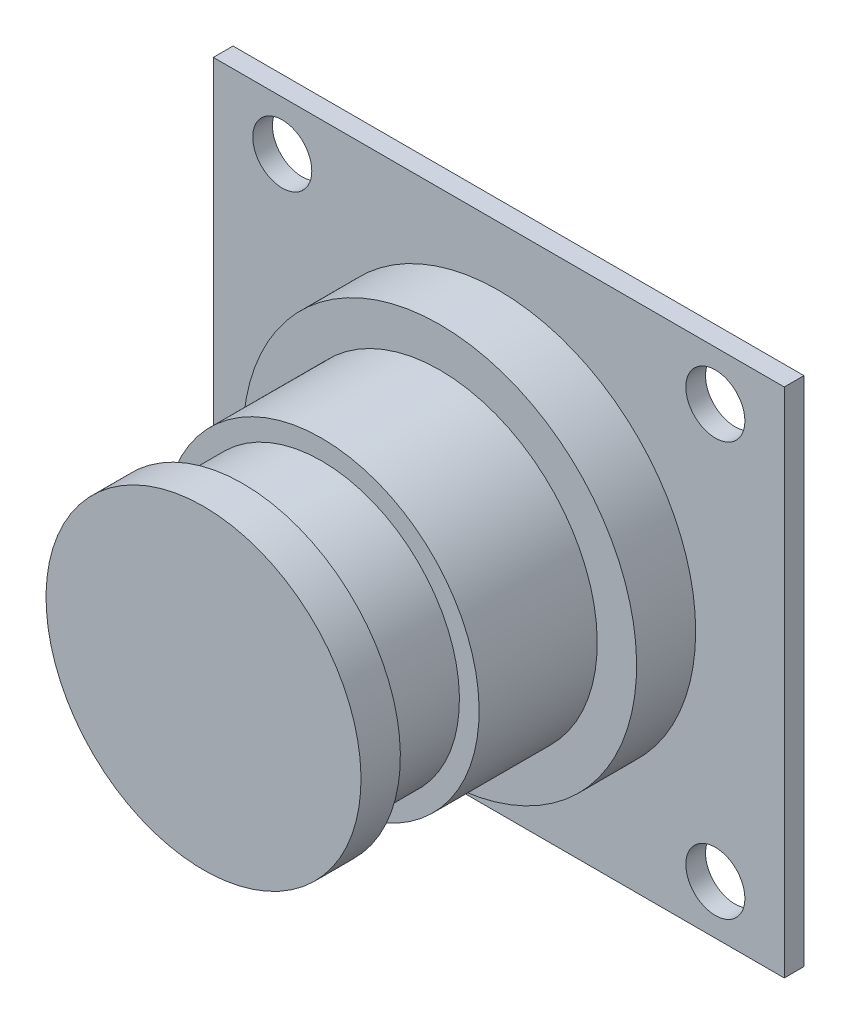
SolidWorks part; units mm, degrees
material "自定义塑料"
ref_plane "前视基准面" through (0, 0, 0) normal (0, 0, 1) x (1, 0, 0)
ref_plane "上视基准面" through (0, 0, 0) normal (0, 1, 0) x (1, 0, 0)
ref_plane "右视基准面" through (0, 0, 0) normal (1, 0, 0) x (0, 0, -1)
other "Configuration Table"
sketch "草图1" plane through (0, 0, 0) normal (0, 0, 1) x (1, 0, 0)
  line L0 (-19.7925, 0) -> (25.058, 0) construction
  line L1 (-14.5, 13) -> (14.5, 13)
  line L2 (-14.5, 13) -> (-14.5, -13)
  line L3 (-14.5, -13) -> (14.5, -13)
  line L4 (14.5, 13) -> (14.5, -13)
  line L5 (-11, 10.5) -> (11, 10.5) construction
  line L6 (-11, 10.5) -> (-11, -10.5) construction
  line L7 (-11, -10.5) -> (11, -10.5) construction
  line L8 (11, 10.5) -> (11, -10.5) construction
  line L9 (0, 23.3134) -> (0, -16.2925) construction
  circle A0 centre (-11, 10.5) radius 1.5
  circle A1 centre (11, 10.5) radius 1.5
  circle A2 centre (11, -10.5) radius 1.5
  circle A3 centre (-11, -10.5) radius 1.5
  dimension "D1" = 3
  dimension "D2" = 26
  dimension "D3" = 29
  dimension "D4" = 21
  dimension "D5" = 22
extrude "凸台-拉伸1" add sketch "草图1" along normal blind 1
sketch "草图2" plane through (0, 0, 0) normal (1, 0, 0) x (0, 0, -1)
  line L0 (-1, 0) -> (-16, 0)
  line L1 (-1, -13) -> (-1, 13) construction
  line L2 (-16, 0) -> (-16, 8)
  line L3 (-16, 8) -> (-14, 8)
  line L4 (-14, 8) -> (-14, 7)
  line L5 (-14, 7) -> (-10, 7)
  line L6 (-10, 7) -> (-10, 8)
  line L7 (-10, 8) -> (-4, 8)
  line L8 (-4, 8) -> (-4, 10)
  line L9 (-4, 10) -> (-1, 10)
  line L10 (-1, 10) -> (-1, 0)
  dimension "D1" = 15
  dimension "D2" = 8
  dimension "D3" = 7
  dimension "D4" = 8
  dimension "D5" = 10
  dimension "D6" = 3
  dimension "D7" = 6
  dimension "D8" = 4
revolve "旋转2" add sketch "草图2" angle 360 about L0
